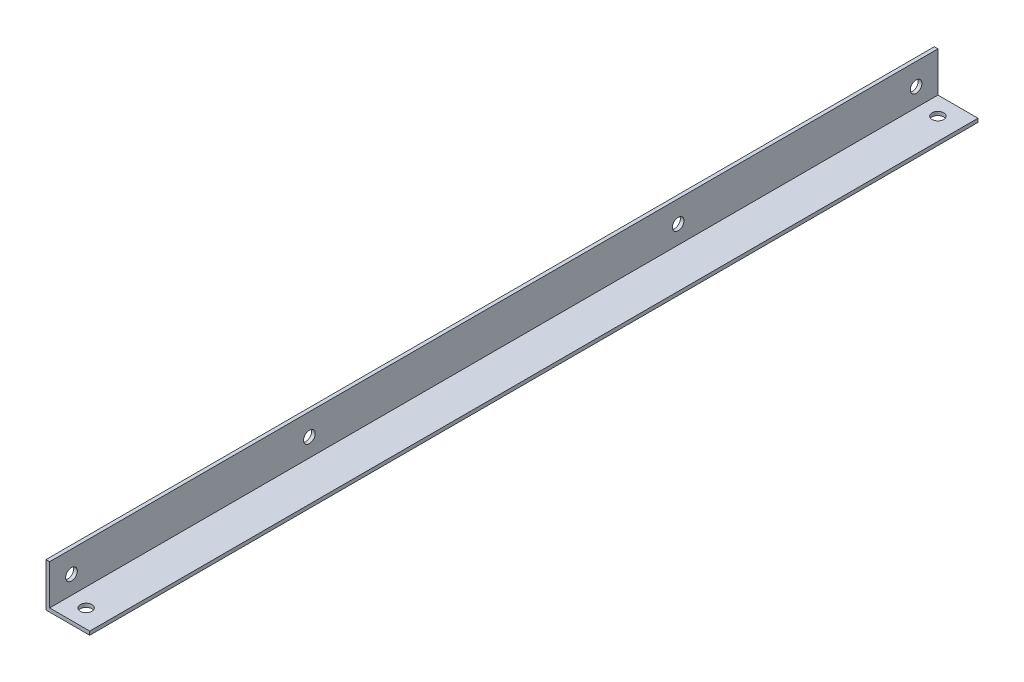
SolidWorks part; units mm, degrees
ref_plane "Front Plane" through (0, 0, 0) normal (0, 0, 1) x (1, 0, 0)
ref_plane "Top Plane" through (0, 0, 0) normal (0, 1, 0) x (1, 0, 0)
ref_plane "Right Plane" through (0, 0, 0) normal (1, 0, 0) x (0, 0, -1)
sketch "Sketch1" plane through (0, 0, 0) normal (0, 0, 1) x (1, 0, 0)
  line L0 (0, 0) -> (0, 30)
  line L1 (0, 30) -> (2.5, 30)
  line L2 (2.5, 30) -> (2.5, 2.5)
  line L3 (2.5, 2.5) -> (30, 2.5)
  line L4 (30, 2.5) -> (30, 0)
  line L5 (30, 0) -> (0, 0)
  dimension "D1" = 2.5
  dimension "D2" = 2.5
  dimension "D3" = 30
  dimension "D4" = 30
extrude "Boss-Extrude1" add sketch "Sketch1" along normal blind 609.6
sketch "Sketch2" plane through (2.5, 0, 0) normal (1, 0, 0) x (0, 0, -1)
  line L0 (0, 30) -> (0, 0) construction
  line L1 (-609.6, 30) -> (-609.6, 0) construction
  line L2 (-304.8, 82.2786) -> (-304.8, -92.2046) construction
  line L3 (-609.6, 2.5) -> (-609.6, 30) construction
  line L4 (-609.6, 30) -> (0, 30) construction
  circle A0 centre (-594.6, 15) radius 4
  circle A1 centre (-15, 15) radius 4
  circle A2 centre (-431.3435, 15) radius 4
  circle A3 centre (-178.2565, 15) radius 4
  dimension "D2" = 8
  dimension "D3" = 15
  dimension "D4" = 15
  dimension "D6" = 8
  dimension "D1" = 15
  dimension "D5" = 15
  dimension "D7" = 416.3435
  dimension "D8" = 178.2565
extrude "Cut-Extrude1" cut sketch "Sketch2" against normal through all
sketch "Sketch3" plane through (0, 2.5, 0) normal (0, 1, 0) x (1, 0, 0)
  line L0 (30, -609.6) -> (30, 0) construction
  line L1 (30, 0) -> (2.5, 0) construction
  line L2 (-108.1269, -304.8) -> (248.8441, -304.8) construction
  circle A0 centre (15, -12.5) radius 4
  circle A1 centre (15, -597.1) radius 4
  dimension "D1" = 8
  dimension "D2" = 15
  dimension "D3" = 12.5
  dimension "D4" = 304.8
extrude "Cut-Extrude2" cut sketch "Sketch3" against normal through all
